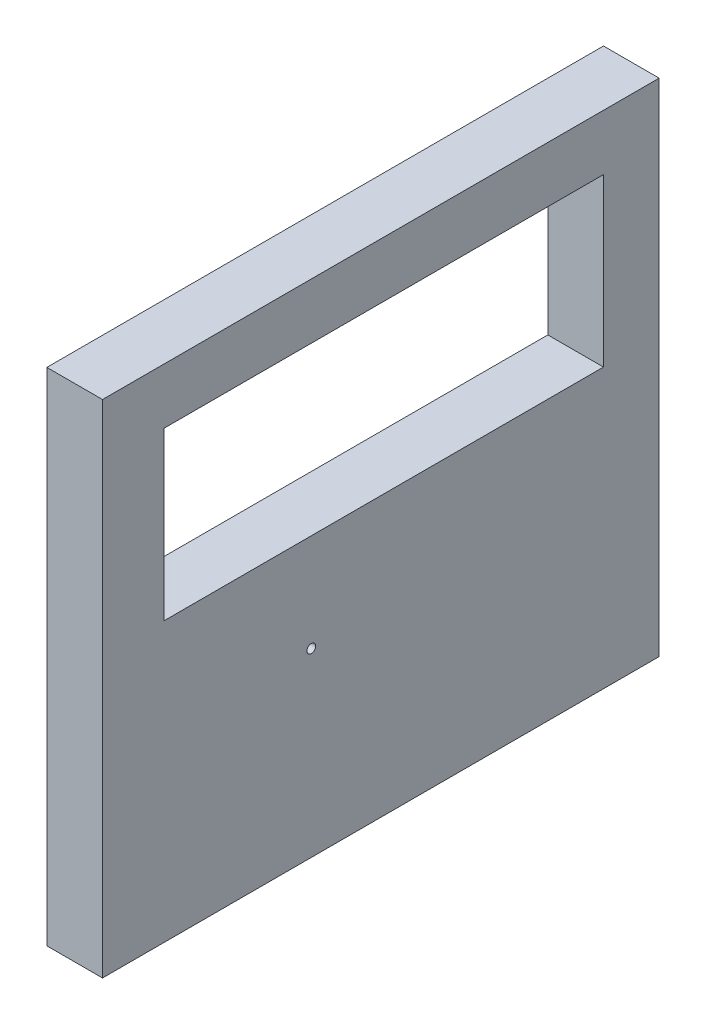
SolidWorks part; units mm, degrees
material "Polyurethane Foam Rigid"
ref_plane "X-Y Datum" through (0, 0, 0) normal (0, 0, 1) x (1, 0, 0)
ref_plane "X-Z Datum" through (0, 0, 0) normal (0, 1, 0) x (1, 0, 0)
ref_plane "Y-Z Datum" through (0, 0, 0) normal (1, 0, 0) x (0, 0, -1)
sketch "Sketch4" plane through (0, 0, 0) normal (0, 0, 1) x (1, 0, 0)
  line L1 (-12.7, -114.3) -> (12.7, -114.3)
  line L2 (-12.7, -114.3) -> (-12.7, 114.3)
  line L3 (-12.7, 114.3) -> (12.7, 114.3)
  line L4 (12.7, -114.3) -> (12.7, 114.3)
  line L5 (-12.7, -114.3) -> (12.7, 114.3) construction
  line L6 (-12.7, 114.3) -> (12.7, -114.3) construction
  point P0 (0, 0)
  dimension "D1" = 25.4
  dimension "D2" = 228.6
extrude "Boss-Extrude1" add sketch "Sketch4" along normal blind 254
sketch "Sketch11" plane through (12.7, 0, 0) normal (1, 0, 0) x (0, 0, -1)
  line L0 (-25.4, 88.9) -> (-25.4, 12.825) construction
  line L1 (-226, 88.9) -> (-25.4, 88.9) construction
  line L2 (-25.4, 12.825) -> (-226, 12.825) construction
  line L3 (-226, 88.9) -> (-226, 12.825) construction
  line L4 (-25.4, 88.9) -> (-25.4, 12.825)
  line L5 (-226, 88.9) -> (-25.4, 88.9)
  line L6 (-25.4, 12.825) -> (-226, 12.825)
  line L7 (-226, 88.9) -> (-226, 12.825)
extrude "Cut-Extrude3" cut sketch "Sketch11" against normal through all contours L5 L7 L6 L4
sketch "Sketch12" plane through (12.7, 0, 0) normal (1, 0, 0) x (0, 0, -1)
  line L0 (-254, -114.3) -> (-254, 114.3) construction
  line L2 (-254, -114.3) -> (0, -114.3) construction
  circle A0 centre (-158.75, -31.75) radius 2
  dimension "D1" = 4
  dimension "D2" = 95.25
  dimension "D3" = 82.55
extrude "Cut-Extrude4" cut sketch "Sketch12" against normal through all
